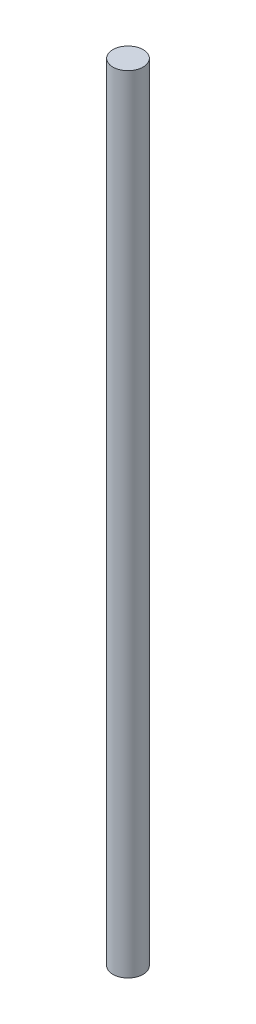
SolidWorks part; units mm, degrees
ref_plane "Front Plane" through (0, 0, 0) normal (0, 0, 1) x (1, 0, 0)
ref_plane "Top Plane" through (0, 0, 0) normal (0, 1, 0) x (1, 0, 0)
ref_plane "Right Plane" through (0, 0, 0) normal (1, 0, 0) x (0, 0, -1)
sketch "Sketch1" plane through (0, 0, 0) normal (0, 1, 0) x (1, 0, 0)
  circle A0 centre (0, 0) radius 3.175
  dimension "D1" = 6.35
extrude "Boss-Extrude1" add sketch "Sketch1" along normal blind 165.1
